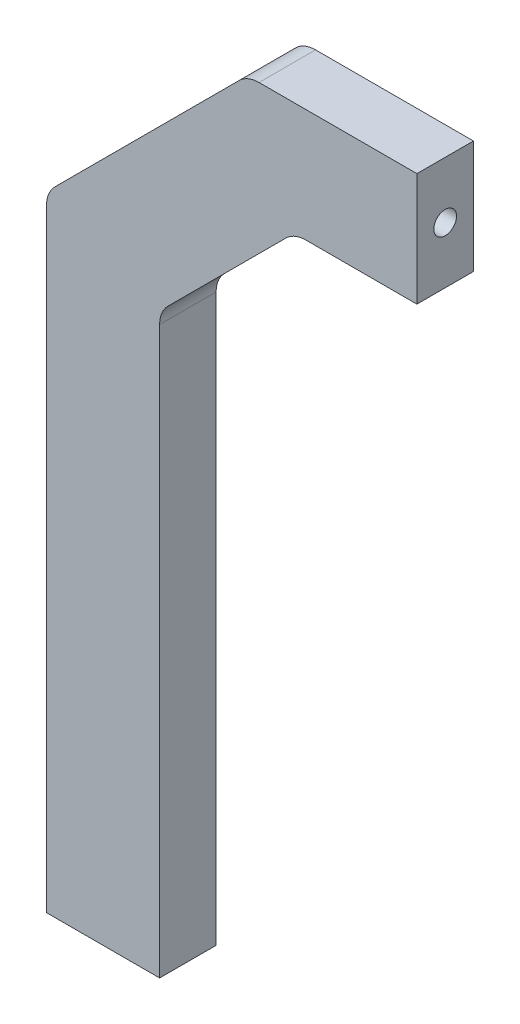
SolidWorks part; units mm, degrees
ref_plane "Front Plane" through (0, 0, 0) normal (0, 0, 1) x (1, 0, 0)
ref_plane "Top Plane" through (0, 0, 0) normal (0, 1, 0) x (1, 0, 0)
ref_plane "Right Plane" through (0, 0, 0) normal (1, 0, 0) x (0, 0, -1)
sketch "Sketch1" plane through (0, 0, 0) normal (0, 0, 1) x (1, 0, 0)
  line L0 (0, 12.7) -> (0, -12.7)
  line L1 (0, 12.7) -> (-38.1, 12.7)
  line L2 (0, -12.7) -> (-27.579, -12.7)
  line L3 (-27.579, -12.7) -> (-57.8104, -42.9314)
  line L4 (-38.1, 12.7) -> (-83.2104, -32.4104)
  line L5 (-60.6552, -9.8552) -> (-42.6947, -27.8157) construction
  line L6 (-27.579, -12.7) -> (-38.1, 12.7) construction
  line L7 (-57.8104, -42.9314) -> (-57.8104, -172.72)
  line L8 (-83.2104, -32.4104) -> (-83.2104, -172.72)
  line L9 (-83.2104, -102.5652) -> (-57.8104, -102.5652) construction
  line L10 (-57.8104, -172.72) -> (-83.2104, -172.72)
  point P2 (0, 0)
  dimension "D1" = 135
  dimension "D2" = 38.1
  dimension "D3" = 25.4
  dimension "D4" = 185.42
  dimension "D5" = 57.8104
extrude "Boss-Extrude1" add sketch "Sketch1" along normal mid plane 12.7
fillet "Fillet1" radius 6.35 4 edges at (-27.579, -12.7, 0) (-57.8104, -42.9314, 0) (-38.1, 12.7, 0) (-83.2104, -32.4104, 0)
hole_wizard "Tap Drill for 1/4-20 Tap1" positions "Sketch2" profile "Sketch4" hole size "1/4-20" standard "ANSI Inch"
sketch "Sketch2" plane through (0, 0, 0) normal (1, 0, 0) x (0, 0, -1)
  point P0 (0, 0)
sketch "Sketch4" plane through (0, 0, 0) normal (0, 1, 0) x (0, 0, -1)
  line L0 (0, 0) -> (0, 14.2338)
  line L1 (0, 14.2338) -> (2.5527, 12.7)
  line L2 (2.5527, 12.7) -> (2.5527, 0)
  line L5 (2.5527, 0) -> (0, 0)
  line L10 (0, 14.2338) -> (-2.5527, 12.7) construction
  line L11 (0, -6.35) -> (0, 107.95) construction
  dimension "Hole Dia." = 5.1054
  dimension "Hole Depth" = 12.7
  dimension "Drill Angle" = 118
hole_wizard "Tap Drill for 1/4-20 Tap2" positions "Sketch5" profile "Sketch6" hole size "1/4-20" standard "ANSI Inch"
sketch "Sketch5" plane through (0, -172.72, 0) normal (0, -1, 0) x (-1, 0, 0)
  line L0 (57.8104, 0) -> (83.2104, 0) construction
  line L1 (57.8104, -6.35) -> (57.8104, 6.35) construction
  line L2 (83.2104, -6.35) -> (83.2104, 6.35) construction
  line L4 (70.5104, 6.35) -> (70.5104, -6.35) construction
  line L5 (83.2104, 6.35) -> (57.8104, 6.35) construction
  line L6 (83.2104, -6.35) -> (57.8104, -6.35) construction
  point P17 (70.5104, 0)
sketch "Sketch6" plane through (-70.5104, -172.72, 0) normal (1, 0, 0) x (0, 0, -1)
  line L0 (0, 0) -> (0, 14.2338)
  line L1 (0, 14.2338) -> (2.5527, 12.7)
  line L2 (2.5527, 12.7) -> (2.5527, 0)
  line L5 (2.5527, 0) -> (0, 0)
  line L10 (0, 14.2338) -> (-2.5527, 12.7) construction
  line L11 (0, -6.35) -> (0, 107.95) construction
  dimension "Hole Dia." = 5.1054
  dimension "Hole Depth" = 12.7
  dimension "Drill Angle" = 118
